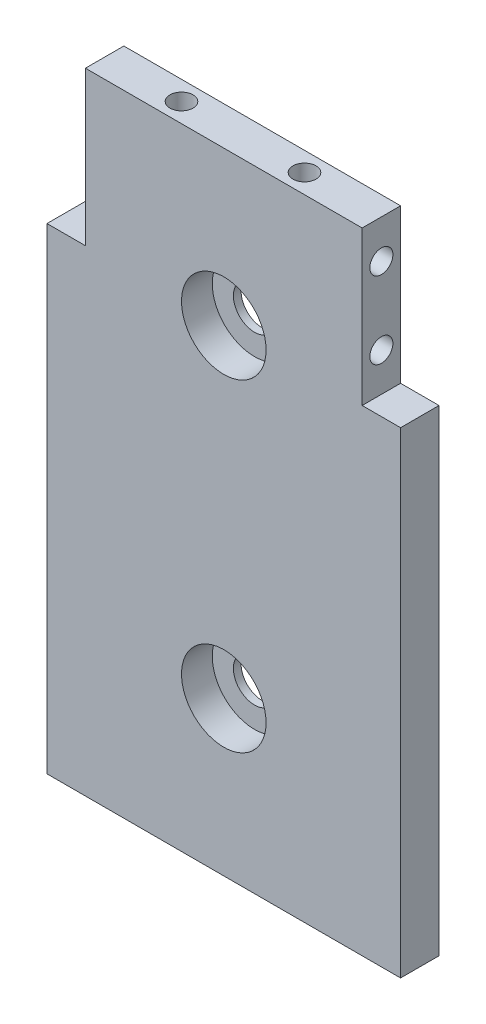
SolidWorks part; units mm, degrees
ref_plane "Front Plane" through (0, 0, 0) normal (0, 0, 1) x (1, 0, 0)
ref_plane "Top Plane" through (0, 0, 0) normal (0, 1, 0) x (1, 0, 0)
ref_plane "Right Plane" through (0, 0, 0) normal (1, 0, 0) x (0, 0, -1)
sketch "Sketch1" plane through (0, 0, 0) normal (0, 0, 1) x (1, 0, 0)
  line L1 (0, 0) -> (46, 0)
  line L2 (0, 0) -> (0, 42)
  line L3 (0, 42) -> (46, 42)
  line L4 (46, 0) -> (46, 42)
  line L5 (0, 42) -> (46, 42)
  line L6 (0, 42) -> (0, 62)
  line L7 (0, 62) -> (46, 62)
  line L8 (46, 42) -> (46, 62)
  line L9 (0, 42) -> (5, 42)
  line L10 (0, 42) -> (0, 0)
  line L11 (0, 0) -> (5, 0)
  line L12 (0, 0) -> (46, 0)
  line L13 (46, 42) -> (41, 42)
  line L14 (46, 42) -> (46, 0)
  line L15 (46, 0) -> (41, 0)
  line L16 (0, 0) -> (0, -20)
  line L17 (0, -20) -> (46, -20)
  line L18 (46, 0) -> (46, -20)
  line L19 (0, 62) -> (5, 62)
  line L20 (0, 62) -> (0, 42)
  line L21 (0, 42) -> (5, 42)
  line L22 (5, 62) -> (5, 42)
  line L23 (46, 62) -> (41, 62)
  line L24 (46, 62) -> (46, 42)
  line L25 (46, 42) -> (41, 42)
  line L26 (41, 62) -> (41, 42)
  circle A2 centre (23, 0) radius 2.75
  circle A3 centre (23, 42) radius 2.75
  dimension "D3" = 5.5
  dimension "D4" = 5.5
  dimension "D1" = 42
  dimension "D2" = 46
  dimension "D5" = 20
  dimension "D6" = 20
  dimension "D7" = 5
  dimension "D8" = 5
extrude "Boss-Extrude1" add sketch "Sketch1" along normal blind 5
sketch "Sketch3" plane through (0, 0, 5) normal (0, 0, 1) x (1, 0, 0)
  circle A0 centre (23, 42) radius 5.5
  circle A1 centre (23, 0) radius 5.5
  dimension "D1" = 11
  dimension "D2" = 11
extrude "Cut-Extrude2" cut sketch "Sketch3" against normal blind 4
sketch "Sketch5" plane through (0, -20, 0) normal (0, -1, 0) x (1, 0, 0)
  line L0 (46, 5) -> (46, 0) construction
  line L1 (0, 5) -> (0, 0) construction
  line L2 (0, 5) -> (46, 5) construction
  circle A0 centre (5, 2.5) radius 1.5
  circle A1 centre (41, 2.5) radius 1.5
  point P6 (0, 2.5)
  dimension "D1" = 3
  dimension "D2" = 3
  dimension "D3" = 5
  dimension "D4" = 5
  dimension "D5" = 2.5
  dimension "D6" = 2.5
extrude "Cut-Extrude3" cut sketch "Sketch5" against normal blind 7
sketch "Sketch6" plane through (5, 0, 0) normal (-1, 0, 0) x (0, 0, 1)
  line L0 (5, 62) -> (5, 42) construction
  line L1 (5, 42) -> (0, 42) construction
  line L2 (5, 62) -> (0, 62) construction
  circle A0 centre (2.5, 47) radius 1.5
  circle A1 centre (2.5, 57) radius 1.5
  dimension "D1" = 3
  dimension "D2" = 3
  dimension "D3" = 2.5
  dimension "D4" = 2.5
  dimension "D5" = 5
  dimension "D6" = 5
extrude "Cut-Extrude4" cut sketch "Sketch6" against normal blind 7
sketch "Sketch7" plane through (41, 0, 0) normal (1, 0, 0) x (0, 0, -1)
  line L0 (0, 62) -> (0, 42) construction
  line L1 (-5, 42) -> (0, 42) construction
  line L2 (-5, 62) -> (0, 62) construction
  circle A0 centre (-2.5, 47) radius 1.5
  circle A1 centre (-2.5, 57) radius 1.5
  dimension "D1" = 3
  dimension "D2" = 3
  dimension "D3" = 2.5
  dimension "D4" = 2.5
  dimension "D5" = 5
  dimension "D6" = 5
extrude "Cut-Extrude5" cut sketch "Sketch7" against normal blind 7
sketch "Sketch8" plane through (0, 62, 0) normal (0, 1, 0) x (1, 0, 0)
  line L0 (5, -5) -> (41, -5) construction
  line L1 (41, -5) -> (41, 0) construction
  line L2 (5, -5) -> (5, 0) construction
  circle A0 centre (15, -2.5) radius 1.5
  circle A1 centre (31, -2.5) radius 1.5
  dimension "D1" = 3
  dimension "D2" = 3
  dimension "D3" = 2.5
  dimension "D4" = 2.5
  dimension "D5" = 10
  dimension "D6" = 10
extrude "Cut-Extrude6" cut sketch "Sketch8" against normal blind 7
